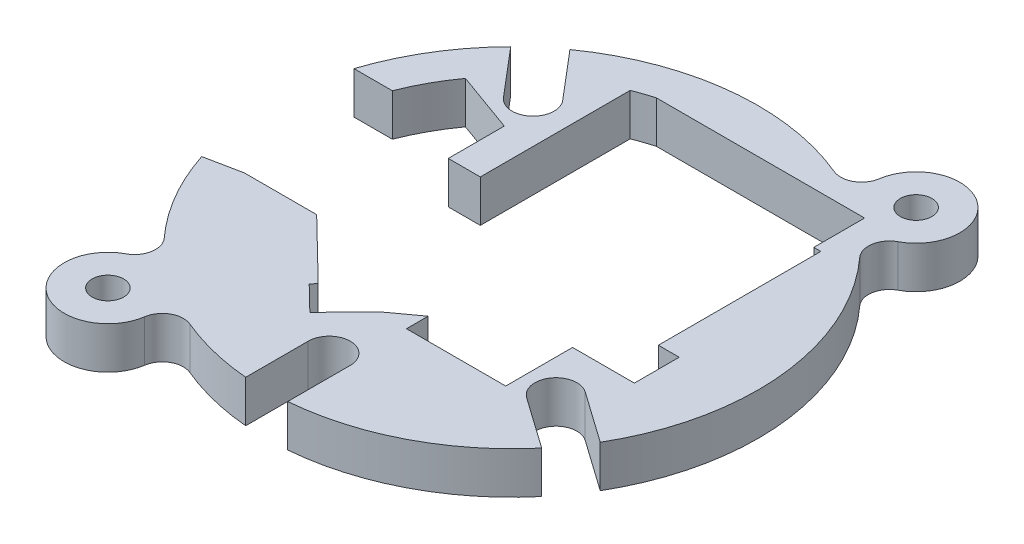
SolidWorks part; units mm, degrees
ref_plane "Front" through (0, 0, 0) normal (0, 0, 1) x (1, 0, 0)
ref_plane "Top" through (0, 0, 0) normal (0, 1, 0) x (1, 0, 0)
ref_plane "Right" through (0, 0, 0) normal (1, 0, 0) x (0, 0, -1)
sketch "Sketch1" plane through (0, 0, 0) normal (0, 1, 0) x (1, 0, 0)
  arc A0 (-16.9841, -5.5245) -> (-16.9841, 5.5245) centre (0, 0) ccw
  line B0 (-12.3326, 8.9535) -> (-7.9248, 7.366)
  line B1 (-7.9248, 3.302) -> (-7.9248, 7.366)
  line B2 (-14.2034, 5.5245) -> (-16.9841, 5.5245)
  line B3 (-16.9841, -5.5245) -> (-14.3951, -5.0038)
  line B4 (-14.3951, -5.0038) -> (-9.1672, -5.0038)
  line B5 (-9.1672, -5.0038) -> (-4.7697, -9.2875)
  line B6 (-4.7697, -9.2875) -> (-5.0932, -9.6195)
  line B7 (-5.0932, -9.6195) -> (-3.2737, -11.3919)
  line B8 (-0.7747, -8.8265) -> (-3.2737, -11.3919)
  line B9 (-0.7747, -8.8265) -> (1.2573, -7.3406)
  line B10 (1.2573, -7.3406) -> (1.2573, -8.9154)
  line B11 (1.2573, -8.9154) -> (8.4582, -8.9154)
  line B12 (8.4582, -4.064) -> (8.4582, -8.9154)
  line B13 (8.4582, -4.064) -> (12.9413, -4.064)
  line B14 (12.9413, -0.8128) -> (12.9413, -4.064)
  line B15 (11.43, -0.8128) -> (12.9413, -0.8128)
  line B16 (11.43, 10.9728) -> (11.43, -0.8128)
  line B17 (10.922, 10.9728) -> (11.43, 10.9728)
  line B18 (10.922, 14.6558) -> (10.922, 10.9728)
  line B19 (-4.1791, 14.6558) -> (10.922, 14.6558)
  line B20 (-5.6007, 14.1736) -> (-5.6007, 3.302)
  line B21 (-5.6007, 3.302) -> (-7.9248, 3.302)
  circle B22 centre (-8.579, 10.1092) radius 1.143
  arc B23 (-12.3326, 8.9535) -> (-14.2034, 5.5245) centre (0, 0) ccw
  arc B24 (-4.1791, 14.6558) -> (-5.6007, 14.1736) centre (0, 0) ccw
  circle B25 centre (10.8325, -7.6454) radius 1.143
  circle B26 centre (0, -13.2588) radius 1.143
sketch_block_instance "ai_pulsar_block_3-1"
sketch_block "ai_pulsar_block_3"
extrude "Boss-Extrude1" add sketch "Sketch1" along normal mid plane 3.048 contours A0 B18 B17 B16 B15 B14 B13 B12 B11 B10 B9 B8 B7 B6 B5 B4 B3 B26 B25 | B24 B19 A0 B2 B23 B0 B1 B21 B20 B22
sketch "Sketch2" plane through (0, 1.524, 0) normal (0, 1, 0) x (1, 0, 0)
  line L0 (-9.741, 9.1231) -> (-12.676, 12.5816)
  line L1 (-7.4171, 11.0953) -> (-10.3521, 14.5538)
  line L2 (-1.524, -13.2588) -> (-1.524, -17.7948)
  line L3 (1.524, -13.2588) -> (1.524, -17.7948)
  line L4 (9.9537, -8.8905) -> (13.6597, -11.5061)
  line L5 (11.7113, -6.4003) -> (15.4173, -9.0159)
  line L6 (1.524, -13.2588) -> (1.524, -17.7948) construction
  circle A0 centre (-8.579, 10.1092) radius 1.524
  circle A1 centre (10.8325, -7.6454) radius 1.524
  circle A2 centre (0, -13.2588) radius 1.524
  arc A3 (-16.9841, -5.5245) -> (10.922, 14.1311) centre (0, 0) ccw construction
  arc A4 (-10.3521, 14.5538) -> (-12.676, 12.5816) centre (0, 0) ccw
  arc A5 (13.6597, -11.5061) -> (15.4173, -9.0159) centre (0, 0) ccw
  arc A6 (-1.524, -17.7948) -> (1.524, -17.7948) centre (0, 0) ccw
  arc M3 (10.2071, 14.6558) -> (-16.9841, 5.5245) centre (0, 0) ccw
  circle M10 centre (-8.579, 10.1092) radius 1.143
  dimension "D1" = 3.048
extrude "Cut-Extrude2" cut sketch "Sketch2" against normal through all contours L2 A6 L3 A2 | L4 A5 L5 A1 | A1 | A0 L1 L0 M3 | A0 M10
sketch "Sketch3" plane through (0, 1.524, 0) normal (0, 1, 0) x (1, 0, 0)
  line L0 (10.2071, 14.6558) -> (10.922, 14.6558)
  line L1 (10.922, 14.6558) -> (10.922, 14.1311)
  line L2 (-4.1791, 14.6558) -> (10.2071, 14.6558) construction
  arc A0 (6.8939, 16.4758) -> (8.9894, 17.656) centre (7.4822, 17.8817) ccw construction
  arc A1 (13.6243, 14.3847) -> (8.9894, 17.656) centre (12.1294, 17.1857) ccw construction
  arc A2 (13.6243, 14.3847) -> (13.2143, 12.015) centre (14.3419, 13.0402) ccw construction
  arc A3 (-13.6243, -14.3847) -> (-13.2143, -12.015) centre (-14.3419, -13.0402) ccw construction
  arc A4 (-13.6243, -14.3847) -> (-8.9894, -17.656) centre (-12.1294, -17.1857) ccw construction
  arc A5 (6.8939, 16.4758) -> (8.9894, 17.656) centre (7.4822, 17.8817) ccw
  arc A6 (13.6243, 14.3847) -> (8.9894, 17.656) centre (12.1294, 17.1857) ccw
  arc A7 (13.6243, 14.3847) -> (13.2143, 12.015) centre (14.3419, 13.0402) ccw
  arc A8 (-13.6243, -14.3847) -> (-13.2143, -12.015) centre (-14.3419, -13.0402) ccw
  arc A9 (-13.6243, -14.3847) -> (-8.9894, -17.656) centre (-12.1294, -17.1857) ccw
  arc A10 (6.8939, 16.4758) -> (10.2071, 14.6558) centre (0, 0) cw
  arc A11 (10.922, 14.1311) -> (13.2143, 12.015) centre (0, 0) cw
  arc A12 (-6.8939, -16.4758) -> (-8.9894, -17.656) centre (-7.4822, -17.8817) ccw construction
  arc A13 (-6.8939, -16.4758) -> (-8.9894, -17.656) centre (-7.4822, -17.8817) ccw
  arc A14 (-13.2143, -12.015) -> (-6.7864, -16.5204) centre (0, 0) ccw
  circle A15 centre (-12.1294, -17.1857) radius 1.143 construction
  circle A16 centre (12.1294, 17.1857) radius 1.143 construction
  circle A17 centre (-12.1294, -17.1857) radius 1.143
  circle A18 centre (12.1294, 17.1857) radius 1.143
  arc M12 (10.2071, 14.6558) -> (-10.3521, 14.5538) centre (0, 0) ccw
extrude "Boss-Extrude2" add sketch "Sketch3" against normal blind 3.048 contours L1 A11 A7 A6 A5 L0 A18 M12 | A14 A8 A9 A13 A17
